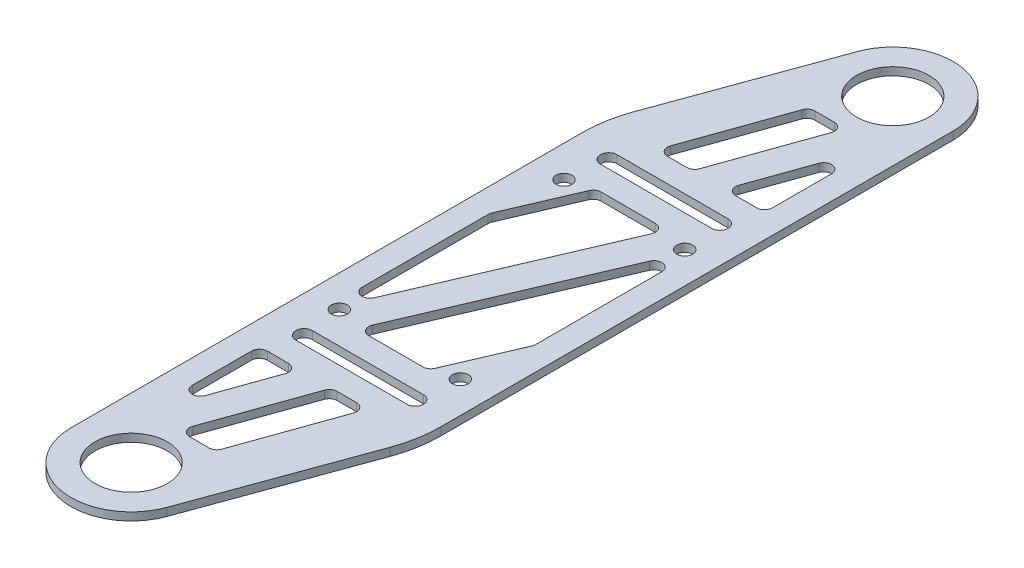
SolidWorks part; units mm, degrees
ref_plane "Front Plane" through (0, 0, 0) normal (0, 0, 1) x (1, 0, 0)
ref_plane "Top Plane" through (0, 0, 0) normal (0, 1, 0) x (1, 0, 0)
ref_plane "Right Plane" through (0, 0, 0) normal (1, 0, 0) x (0, 0, -1)
sketch "Sketch1" plane through (0, 0, 0) normal (0, 1, 0) x (1, 0, 0)
  line L0 (-22.225, 60.96) -> (22.225, 60.96) construction
  line L1 (-22.225, -60.96) -> (22.225, -60.96) construction
  line L2 (-36.83, -139.7) -> (-36.83, 65.0236)
  line L3 (9.9748, -147.9529) -> (33.7664, -82.5861)
  line L4 (56.9672, 0) -> (-57.3606, 0) construction
  line L5 (-22.225, -64.262) -> (22.225, -64.262)
  line L6 (-22.225, -57.658) -> (22.225, -57.658)
  line L8 (36.83, -65.2114) -> (36.83, 139.7)
  line L9 (-33.7664, 82.3982) -> (-9.3126, 149.5844)
  line L15 (-22.225, 64.262) -> (22.225, 64.262)
  line L16 (-22.225, 57.658) -> (22.225, 57.658)
  circle A0 centre (12.7, 139.7) radius 14.478
  arc A1 (-36.83, -139.7) -> (9.9748, -147.9529) centre (-12.7, -139.7) ccw
  arc A2 (36.83, 139.7) -> (-10.5162, 146.2776) centre (12.7, 139.7) ccw
  circle A3 centre (-12.7, -139.7) radius 14.478
  arc A4 (-36.83, 65.0236) -> (-33.7664, 82.3982) centre (13.97, 65.0236) cw
  arc A5 (33.7664, -82.5861) -> (36.83, -65.2114) centre (-13.97, -65.2114) ccw
  arc A6 (-22.225, 64.262) -> (-22.225, 57.658) centre (-22.225, 60.96) ccw
  arc A7 (22.225, 57.658) -> (22.225, 64.262) centre (22.225, 60.96) ccw
  arc A8 (-22.225, -64.262) -> (-22.225, -57.658) centre (-22.225, -60.96) cw
  arc A9 (22.225, -57.658) -> (22.225, -64.262) centre (22.225, -60.96) cw
  circle A10 centre (-24.13, 44.958) radius 3.175
  circle A11 centre (24.2421, -44.8976) radius 3.175
  circle A12 centre (24.2421, 44.8976) radius 3.175
  circle A13 centre (-24.13, -44.958) radius 3.175
  point P16 (0, -60.96)
  point P29 (0, 60.96)
  point P39 (0, 0)
  dimension "D1" = 24.13
  dimension "D3" = 50.8
  dimension "D5" = 28.956
  dimension "D6" = 24.13
  dimension "D8" = 12.7
  dimension "D2" = 50.8
  dimension "D12" = 2
  dimension "D4" = 49.53
  dimension "D7" = 279.4
  dimension "D10" = 24.13
  dimension "D11" = 119.888
extrude "Boss-Extrude1" add sketch "Sketch1" along normal blind 3.175 contours L3 A5 L8 A2 L9 A4 L2 A1 A11 A10 A7 L16 A6 L15 A0 A3 L6 A9 L5 A8
sketch "Sketch2" plane through (0, 3.175, 0) normal (0, 1, 0) x (1, 0, 0)
  line L0 (-27.305, 17.7805) -> (-27.305, -32.6709)
  line L1 (-21.2119, -33.922) -> (12.0722, 43.7068)
  line L2 (9.1542, 48.133) -> (-12.4774, 48.133)
  line L3 (27.305, -17.7805) -> (27.305, 32.6709)
  line L4 (21.2119, 33.922) -> (-12.0722, -43.7068)
  line L5 (-15.7259, -73.787) -> (-24.13, -73.787)
  line L7 (-9.1542, -48.133) -> (12.4774, -48.133)
  line L8 (15.3955, -46.2092) -> (27.0481, -19.0317)
  line L10 (-27.305, -76.962) -> (-27.305, -100.5948)
  line L11 (-9.9908, -118.999) -> (-2.2407, -118.999)
  line L12 (0.7508, -116.8878) -> (14.5706, -78.0258)
  line L13 (11.5791, -73.787) -> (3.8291, -73.787)
  line L14 (-22.225, -64.262) -> (22.225, -64.262) construction
  line L15 (-21.1385, -101.6586) -> (-12.7344, -78.0258)
  line L16 (0.8376, -75.8982) -> (-12.9822, -114.7602)
  line L17 (15.7259, 73.787) -> (24.13, 73.787)
  line L18 (27.305, 76.962) -> (27.305, 100.5948)
  line L19 (9.9908, 118.999) -> (2.2407, 118.999)
  line L20 (-0.7508, 116.8878) -> (-14.5706, 78.0258)
  line L21 (-11.5791, 73.787) -> (-3.8291, 73.787)
  line L22 (21.1385, 101.6586) -> (12.7344, 78.0258)
  line L23 (-0.8376, 75.8982) -> (12.9822, 114.7602)
  line L24 (-15.3955, 46.2092) -> (-27.0481, 19.0317)
  arc A0 (9.1542, 48.133) -> (12.0722, 43.7068) centre (9.1542, 44.958) cw
  arc A1 (-21.2119, -33.922) -> (-27.305, -32.6709) centre (-24.13, -32.6709) cw
  arc A2 (-12.4774, 48.133) -> (-15.3955, 46.2092) centre (-12.4774, 44.958) ccw
  arc A3 (-9.1542, -48.133) -> (-12.0722, -43.7068) centre (-9.1542, -44.958) cw
  arc A4 (21.2119, 33.922) -> (27.305, 32.6709) centre (24.13, 32.6709) cw
  arc A5 (-27.0481, 19.0317) -> (-27.305, 17.7805) centre (-24.13, 17.7805) ccw
  arc A6 (0.8376, -75.8982) -> (3.8291, -73.787) centre (3.8291, -76.962) cw
  arc A7 (14.5706, -78.0258) -> (11.5791, -73.787) centre (11.5791, -76.962) ccw
  arc A8 (-2.2407, -118.999) -> (0.7508, -116.8878) centre (-2.2407, -115.824) ccw
  arc A9 (-9.9908, -118.999) -> (-12.9822, -114.7602) centre (-9.9908, -115.824) cw
  arc A10 (-21.1385, -101.6586) -> (-27.305, -100.5948) centre (-24.13, -100.5948) cw
  arc A11 (-15.7259, -73.787) -> (-12.7344, -78.0258) centre (-15.7259, -76.962) cw
  arc A12 (-27.305, -76.962) -> (-24.13, -73.787) centre (-24.13, -76.962) cw
  arc A13 (-0.8376, 75.8982) -> (-3.8291, 73.787) centre (-3.8291, 76.962) cw
  arc A14 (-14.5706, 78.0258) -> (-11.5791, 73.787) centre (-11.5791, 76.962) ccw
  arc A15 (2.2407, 118.999) -> (-0.7508, 116.8878) centre (2.2407, 115.824) ccw
  arc A16 (9.9908, 118.999) -> (12.9822, 114.7602) centre (9.9908, 115.824) cw
  arc A17 (21.1385, 101.6586) -> (27.305, 100.5948) centre (24.13, 100.5948) cw
  arc A18 (15.7259, 73.787) -> (12.7344, 78.0258) centre (15.7259, 76.962) cw
  arc A19 (27.305, 76.962) -> (24.13, 73.787) centre (24.13, 76.962) cw
  arc A20 (12.4774, -48.133) -> (15.3955, -46.2092) centre (12.4774, -44.958) ccw
  arc A21 (27.0481, -19.0317) -> (27.305, -17.7805) centre (24.13, -17.7805) ccw
  arc A22 (-9.1542, -48.133) -> (-12.0722, -43.7068) centre (-9.1542, -44.958) cw [skipped]
  arc A23 (21.2119, 33.922) -> (27.305, 32.6709) centre (24.13, 32.6709) cw [skipped]
  point P15 (0, 0)
  point P21 (0, 0)
  point P23 (0, 0)
  point P25 (0, 0)
  point P29 (0, 0)
  point P36 (0, -64.262)
  point P50 (-11.227, -73.787)
  point P55 (0, 0)
  point P77 (0, 0)
  point P80 (0, 0)
  point P81 (0, 0)
  dimension "D5" = 3.175
  dimension "D6" = 9.525
  dimension "D7" = 3.175
  dimension "D9" = 3.175
  dimension "D1" = 13.6521
  dimension "D4" = 2
  dimension "D8" = 2
extrude "Cut-Extrude1" cut sketch "Sketch2" against normal through all
